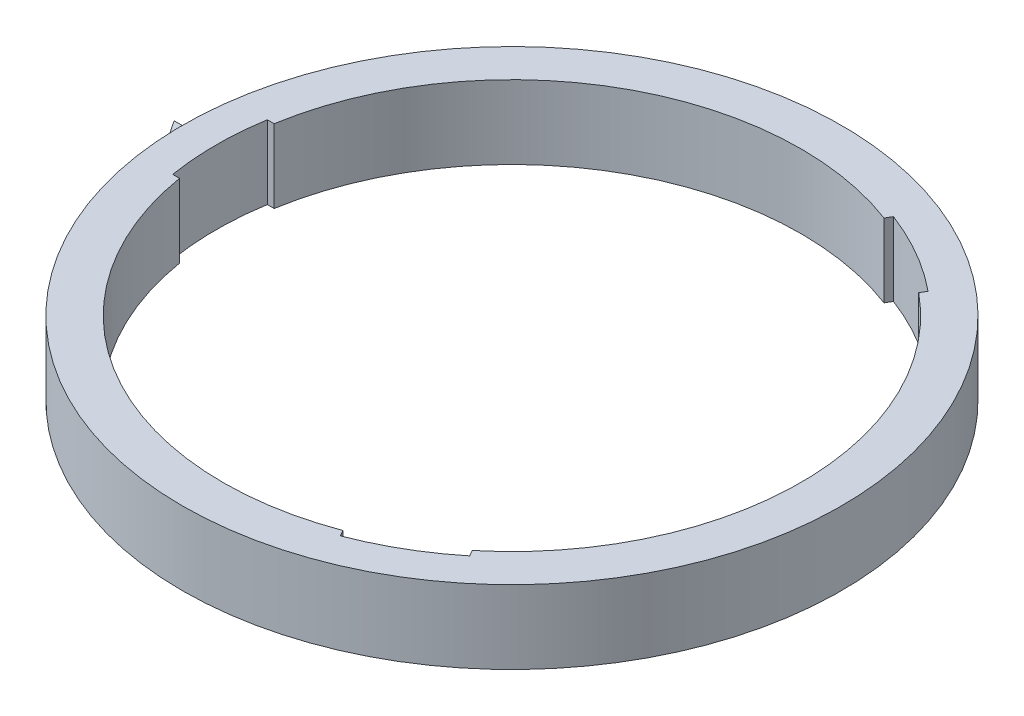
SolidWorks part; units mm, degrees
ref_plane "Front Plane" through (0, 0, 0) normal (0, 0, 1) x (1, 0, 0)
ref_plane "Top Plane" through (0, 0, 0) normal (0, 1, 0) x (1, 0, 0)
ref_plane "Right Plane" through (0, 0, 0) normal (1, 0, 0) x (0, 0, -1)
sketch "Sketch1" plane through (0, 0, 0) normal (0, 1, 0) x (1, 0, 0)
  circle A0 centre (0, 0) radius 19.5
  circle A1 centre (0, 0) radius 17.1
  dimension "D1" = 39
  dimension "D2" = 34.2
extrude "Boss-Extrude1" add sketch "Sketch1" along normal blind 4.3478
ref_plane "Plane1" through (-19.5, 0, 0) normal (-1, 0, 0) x (0, 0, 1)
sketch "Sketch2" plane through (-19.5, 0, 0) normal (-1, 0, 0) x (0, 0, 1)
  line L2 (0, 0.0093) -> (-1.087, 2.1739)
  line L3 (1.087, 2.1739) -> (0, 0.0093)
  line L4 (0, 4.3385) -> (-1.087, 2.1739)
  line L5 (1.087, 2.1739) -> (0, 4.3385)
  point P9 (0, 2.1739)
  point P12 (0, 2.1739)
extrude "Boss-Extrude2" add sketch "Sketch2" along normal mid plane 2.1739
chamfer "Chamfer1" distance 0.6 distance2 0.971 4 edges at (-20.587, 3.2562, 0.5435) (-20.587, 1.0916, 0.5435) (-20.587, 1.0916, -0.5435) (-20.587, 3.2562, -0.5435)
sketch "Sketch3" plane through (0, 4.3478, 0) normal (0, 1, 0) x (1, 0, 0)
  line L6 (-17.2745, 2.8) -> (-15.7531, 2.8)
  line L7 (-17.2745, -2.8) -> (-15.7531, -2.8)
  line L8 (11.0621, 13.5602) -> (10.3014, 12.2426)
  line L9 (6.2124, 16.3602) -> (5.4517, 15.0426)
  line L10 (6.2124, -16.3602) -> (5.4517, -15.0426)
  line L11 (11.0621, -13.5602) -> (10.3014, -12.2426)
  arc A6 (-15.7531, 2.8) -> (-15.7531, -2.8) centre (0, 0) ccw
  arc A7 (-17.2745, 2.8) -> (-17.2745, -2.8) centre (0, 0) ccw
  arc A8 (10.3014, 12.2426) -> (5.4517, 15.0426) centre (0, 0) ccw
  arc A9 (11.0621, 13.5602) -> (6.2124, 16.3602) centre (0, 0) ccw
  arc A10 (5.4517, -15.0426) -> (10.3014, -12.2426) centre (0, 0) ccw
  arc A11 (6.2124, -16.3602) -> (11.0621, -13.5602) centre (0, 0) ccw
  point P15 (0, 0)
  dimension "D2" = 32
  dimension "D1" = 1.5
  dimension "D3" = 2.8
  dimension "D4" = 2.8
  dimension "D5" = 3
extrude "Cut-Extrude1" cut sketch "Sketch3" against normal through all
equation "\"clearance\"= 0.3mm ' Freely and easily sliding. Used as a gap between the telescopic sections."
equation "\"clearance2\" = 0.1mm ' Used as a gap between rings next to each other."
equation "\"interference\"= 0.1mm ' This is like clearance1 but when two parts should just fit together rather than freely spin."
equation "\"D2@Sketch1\"=34.00mm+\"interference\" * 2"
equation "\"clearance1\" = 0.3mm ' Sliding but a little resistance. Used as a gap between the core and the rotating rings."
equation "\"pegLength\"= 1.5mm ' The length of the pegs that stick out from the telescopic sections."
equation "\"D1@Sketch3\"=\"pegLength\""
equation "\"D3@Sketch3\"=\"clearance\" + 2.5"
equation "\"D4@Sketch3\"=\"clearance\" + 2.5"
